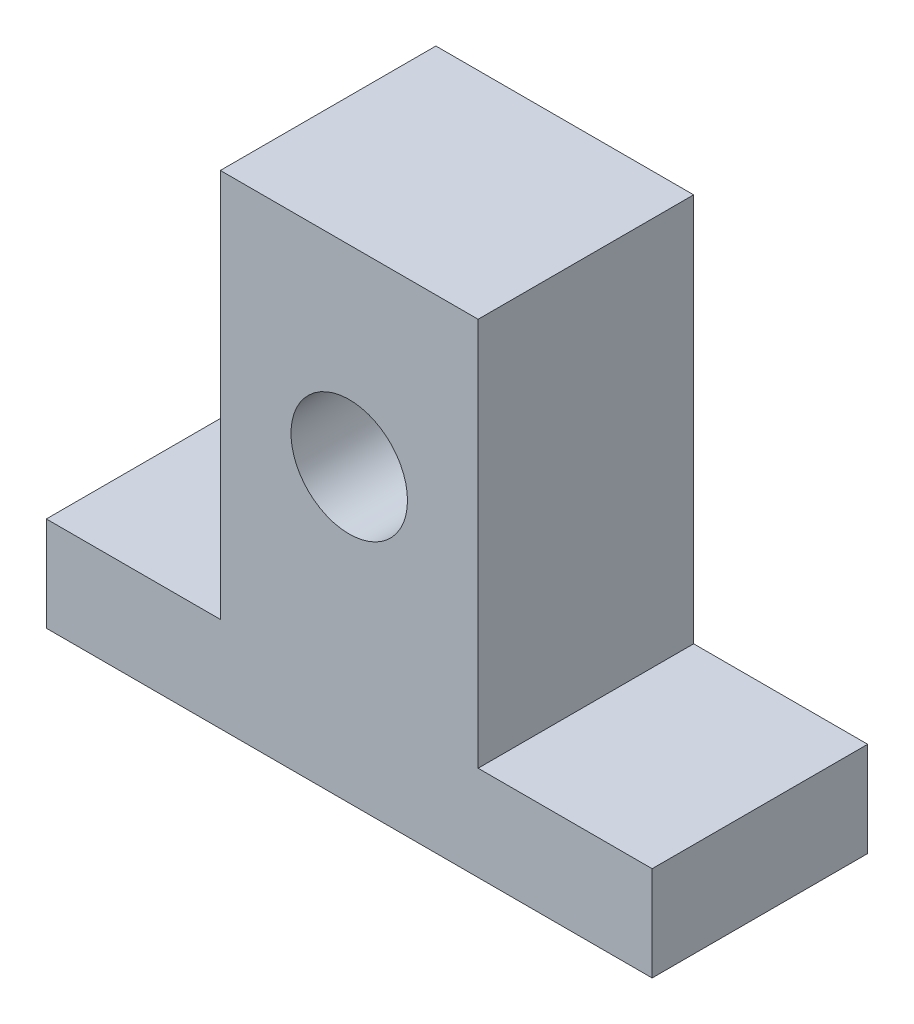
SolidWorks part; units mm, degrees
ref_plane "Front Plane" through (0, 0, 0) normal (0, 0, 1) x (1, 0, 0)
ref_plane "Top Plane" through (0, 0, 0) normal (0, 1, 0) x (1, 0, 0)
ref_plane "Right Plane" through (0, 0, 0) normal (1, 0, 0) x (0, 0, -1)
sketch "Sketch1" plane through (0, 0, 0) normal (0, 0, 1) x (1, 0, 0)
  line L0 (-20.8, 0) -> (20.8, 0)
  line L1 (20.8, 0) -> (20.8, 6.5)
  line L2 (20.8, 6.5) -> (8.85, 6.5)
  line L3 (8.85, 6.5) -> (8.85, 33.2)
  line L4 (8.85, 33.2) -> (-8.85, 33.2)
  line L5 (-8.85, 33.2) -> (-8.85, 6.5)
  line L6 (-8.85, 6.5) -> (-20.8, 6.5)
  line L7 (-20.8, 6.5) -> (-20.8, 0)
  circle A0 centre (0, 20) radius 4
  dimension "D8" = 8
  dimension "D1" = 41.6
  dimension "D2" = 6.5
  dimension "D3" = 6.5
  dimension "D4" = 17.7
  dimension "D5" = 11.95
  dimension "D6" = 33.2
  dimension "D7" = 8.85
  dimension "D9" = 20
  dimension "D10" = 8.85
extrude "Boss-Extrude1" add sketch "Sketch1" along normal blind 14.8
